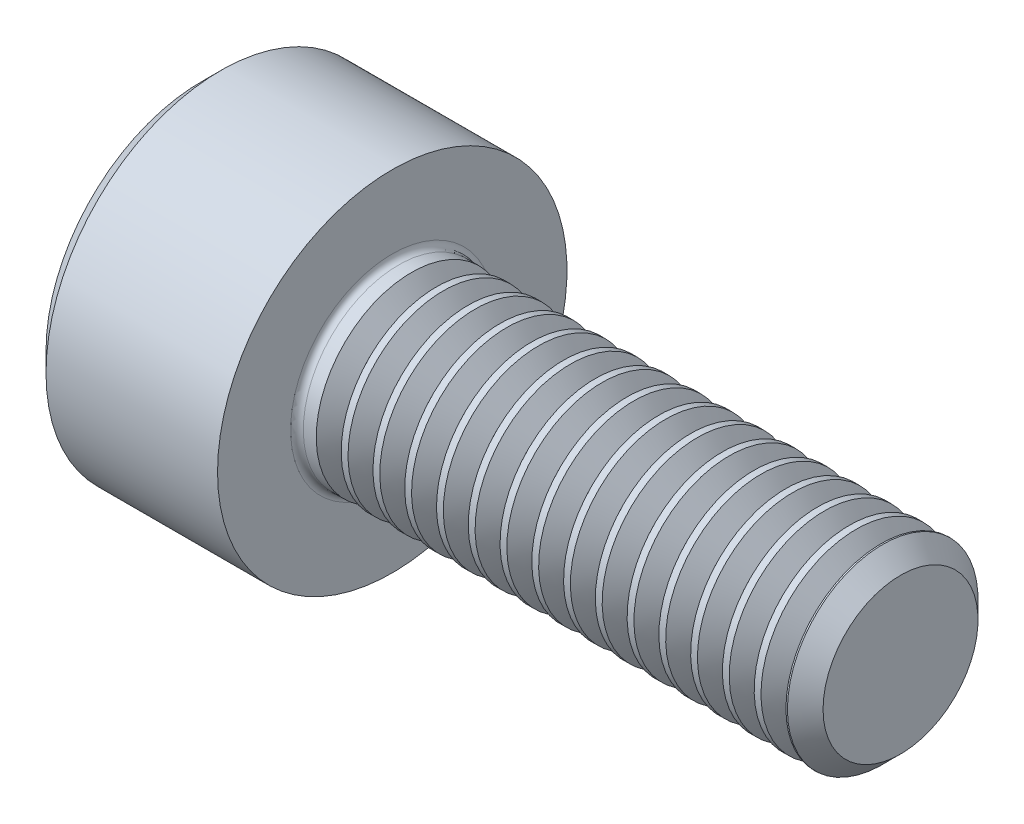
SolidWorks part; units mm, degrees
revolve "Base-Revolve" add sketch "BodySke"
sketch "BodySke" plane through (0, 0, 0) normal (0, 0, 1) x (1, 0, 0)
  line L0 (0, 0) -> (0, 2.45)
  line L1 (0.3, 2.75) -> (3, 2.75)
  line L2 (3, 2.75) -> (3, 1.5)
  line L3 (3, 1.5) -> (10.7195, 1.5)
  line L4 (11, 1.2195) -> (11, 0)
  line L5 (11, 0) -> (0, 0)
  line L6 (-31.75, 0) -> (127, 0) construction
  line L7 (0, 2.45) -> (0.3, 2.75)
  line L8 (11, 1.2195) -> (10.7195, 1.5)
  line L9 (0, -2.45) -> (0.3, -2.75) construction
  line L10 (11, -1.2195) -> (10.7195, -1.5) construction
  line L11 (3.5, 9.525) -> (3.5, 3.175) construction
  line L12 (3, 9.525) -> (3, 3.175) construction
  line L13 (-39, 9.525) -> (-39, 3.175) construction
  dimension "Diameter" = 3
  dimension "Head_ht" = 3
  dimension "Length" = 8
  dimension "Body_ch_ang" = 45
  dimension "Head_dia" = 5.5
  dimension "Head_ch_ang" = 45
  dimension "Minor_dia" = 2.439
  dimension "Advance" = 0.5
  dimension "Thread_nom" = 8
  dimension "Thread_length" = 50
  dimension "Head_ch_ht" = 0.3
cosmetic thread "ThreadCosmetic" [suppressed]
fillet "Fillet1" radius 0.1 1 edges at (3, 0, 1.5)
ref_plane "Plane1" through (0, 0, 0) normal (0, 0, 1) x (1, 0, 0)
ref_plane "Plane2" through (0, 0, 0) normal (0, 1, 0) x (1, 0, 0)
ref_plane "Plane3" through (0, 0, 0) normal (1, 0, 0) x (0, 0, -1)
sketch "Sketch2" plane through (0, 0, 0) normal (0, 0, 1) x (1, 0, 0)
  line L0 (0, 1.28) -> (1.3, 1.28)
  line L1 (1.3, 1.28) -> (2.039, 0)
  line L2 (-31.75, 0) -> (127, 0) construction
  line L3 (2.039, 0) -> (0, 0)
  line L4 (0, 0) -> (0, 1.28)
  line L5 (0, 2.45) -> (0, -2.45) construction
  line L6 (0, 0) -> (47.625, 0) construction
  line L7 (3, -2.75) -> (3, 2.75) construction
  dimension "D1" = 1.28
  dimension "D2" = 60
revolve "Hex-PreBroach" cut sketch "Sketch2" angle 360 about L6
sketch "Sketch3" plane through (0, 0, 0) normal (-1, 0, 0) x (0, 0.5, 0.866)
  line L0 (0.739, 1.28) -> (-0.739, 1.28)
  line L1 (-0.739, 1.28) -> (-1.478, 0)
  line L2 (0.739, 1.28) -> (1.478, 0)
  line L3 (0.739, -1.28) -> (1.478, 0)
  line L4 (0.739, -1.28) -> (-0.739, -1.28)
  line L5 (-0.739, -1.28) -> (-1.478, 0)
  dimension "D1" = 1.28
  dimension "D2" = 1.28
  dimension "Hex_size" = 2.56
extrude "Hex" cut sketch "Sketch3" against normal blind 1.3
sketch "Sketch4" plane through (0, 0, 0) normal (-1, 0, 0) x (0, 0, 1)
  line L0 (0, 0) -> (1.4605, 0)
  line L1 (0, 0) -> (6.1484, 3.5498) construction
  line L2 (0, 0) -> (0.7302, 1.2648)
  line L3 (1.2009, 0.3267) -> (1.3933, 0.4378)
  line L4 (0.8834, 0.8767) -> (1.0758, 0.9877)
  arc A0 (1.2009, 0.3267) -> (0.8834, 0.8767) centre (0, 0) ccw
  arc A1 (1.4605, 0) -> (1.3933, 0.4378) centre (0, 0) ccw
  arc A2 (0.7302, 1.2648) -> (1.0758, 0.9877) centre (0, 0) cw
  dimension "D1" = 30
  dimension "D2" = 60
  dimension "Spline_p_dim" = 0.635
  dimension "D3" = 0.3175
extrude "Spline" [suppressed] cut sketch "Sketch4" against normal blind 1.3
pattern_circular "CirPattern1" [suppressed] count 6 every 60
sketch "Sketch5" plane through (0, 0, 0) normal (0, 0, 1) x (1, 0, 0)
  line L0 (-31.75, 0) -> (127, 0) construction
  line L2 (0, 2.45) -> (0, -2.45) construction
  circle A0 centre (1.2, 0) radius 0.475
  dimension "Drilled_hole_dia" = 0.95
  dimension "Drilled_hole_loc" = 1.2
extrude "Hole" [suppressed] cut sketch "Sketch5" against normal through all and the other way through all
pattern_circular "Drilled-4" [suppressed] count 2 every 60
pattern_circular "Drilled-6" [suppressed] count 3 every 60
sketch "ThdSchSke" plane through (0, 0, 0) normal (0, 0, 1) x (1, 0, 0)
  line L0 (3.5, -1.2195) -> (3.3036, -1.5)
  line L1 (3.5, -1.2195) -> (3.6964, -1.5)
  line L2 (3.6964, -1.5) -> (3.6964, -1.875)
  line L3 (-3.175, 0) -> (5.1513, 0) construction
  line L5 (3.6964, -1.875) -> (3.3036, -1.875)
  line L6 (3.3036, -1.875) -> (3.3036, -1.5)
  line L7 (0, 2.45) -> (0, -2.45) construction
  dimension "Thread_minor" = 2.439
  dimension "Diameter" = 3
  dimension "Start" = 3.5
revolve "ThreadSchematic" cut sketch "ThdSchSke" angle 360 about L3
pattern_linear "ThdSchPat" count 15 spacing 0.5 along (1, 0, 0) of "ThreadSchematic"
equation "\"D2@Sketch3\" = \"Hex_size@Sketch3\" / 2"
equation "\"D1@Sketch3\" = \"Hex_size@Sketch3\" / 2"
equation "\"D1@Sketch2\" = \"Hex_size@Sketch3\" / 2"
equation "\"D3@Sketch4\" = \"Spline_p_dim@Sketch4\" / 2"
equation "\"Thread_minor@ThreadCosmetic\"  =  \"Minor_dia@BodySke\""
equation "\"D2@CirPattern1\" = 360 / \"Num_teeth@CirPattern1\""
equation "\"Wall_thickness@Sketch2\" = \"Head_ht@BodySke\" - \"Key_eng@Hex\""
equation "\"Thread_length@ThreadCosmetic\" = ((sgn( (\"Length@BodySke\" - \"Advance@BodySke\" ) - \"Thread_nom@BodySke\" )-1)*( (\"Length@BodySke\" - \"Advance@BodySke\" ) - \"Thread_nom@BodySke\" ))/-2+ \"Thread_nom@BodySke\""
equation "\"Thread_minor@ThdSchSke\" = \"Minor_dia@BodySke\""
equation "\"Diameter@ThdSchSke\" = \"Diameter@BodySke\""
equation "\"Overcut@ThdSchSke\" = \"Diameter@BodySke\" * 1.25"
equation "\"Start@ThdSchSke\" = \"Head_ht@BodySke\" + \"Length@BodySke\" - \"Thread_length@ThreadCosmetic\"  '---Non-countersunk---"
equation "\"Num_threads@ThdSchPat\" = int( \"Thread_length@ThreadCosmetic\" / \"Advance@BodySke\" + 0.999 )  + 1"
equation "\"Advance@ThdSchPat\" = \"Thread_length@ThreadCosmetic\" /  (\"Num_threads@ThdSchPat\" - 1) 'relax it"
equation "\"Num_threads@ThdSchPat\" = \"Num_threads@ThdSchPat\" - sgn( \"Num_threads@ThdSchPat\" - 1) '---chamfered tips only---"
